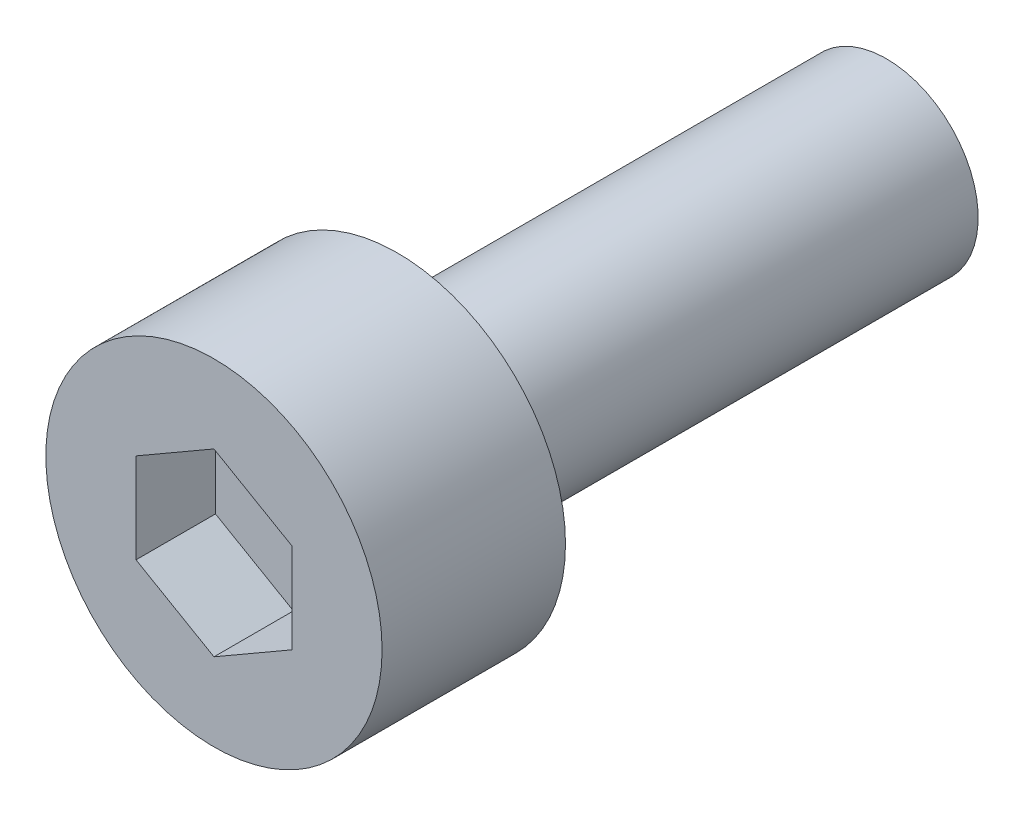
SolidWorks part; units mm, degrees
material "AISI 304"
ref_plane "Front Plane" through (0, 0, 0) normal (0, 0, 1) x (1, 0, 0)
ref_plane "Top Plane" through (0, 0, 0) normal (0, 1, 0) x (1, 0, 0)
ref_plane "Right Plane" through (0, 0, 0) normal (1, 0, 0) x (0, 0, -1)
sketch "草图1" plane through (0, 0, 0) normal (0, 0, 1) x (1, 0, 0)
  circle A0 centre (0, 0) radius 2.75
  dimension "D1" = 5.5
extrude "凸台-拉伸1" add sketch "草图1" along normal blind 3
sketch "草图2" plane through (0, 0, 3) normal (0, 0, 1) x (1, 0, 0)
  line L1 (1.275, -0.7361) -> (1.275, 0.7361)
  line L2 (1.275, 0.7361) -> (0, 1.4722)
  line L3 (0, 1.4722) -> (-1.275, 0.7361)
  line L4 (-1.275, 0.7361) -> (-1.275, -0.7361)
  line L5 (-1.275, -0.7361) -> (0, -1.4722)
  line L6 (0, -1.4722) -> (1.275, -0.7361)
  circle A0 centre (0, 0) radius 1.275 construction
  dimension "D1" = 2.55
extrude "切除-拉伸1" cut sketch "草图2" against normal blind 1.3
sketch "草图3" plane through (0, 0, 0) normal (0, 0, -1) x (-1, 0, 0)
  circle A0 centre (0, 0) radius 1.5
  dimension "D1" = 3
extrude "凸台-拉伸2" add sketch "草图3" along normal blind 8
cosmetic thread "装饰螺纹线1"
